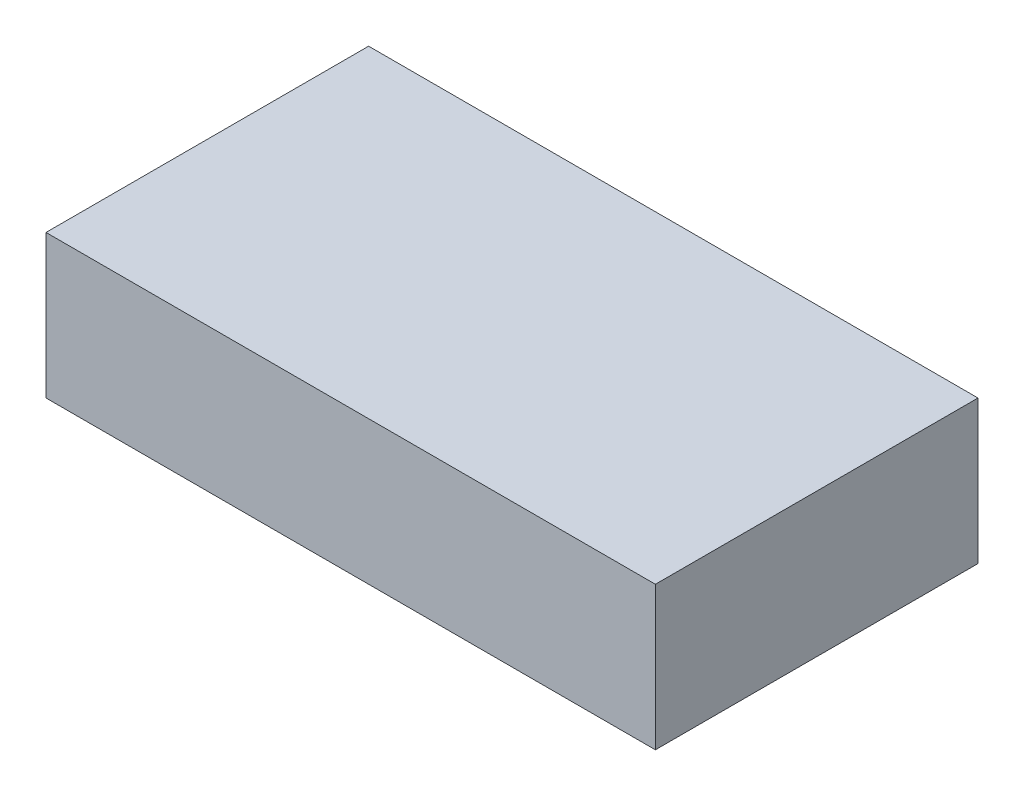
SolidWorks part; units mm, degrees
ref_plane "Front Plane" through (0, 0, 0) normal (0, 0, 1) x (1, 0, 0)
ref_plane "Top Plane" through (0, 0, 0) normal (0, 1, 0) x (1, 0, 0)
ref_plane "Right Plane" through (0, 0, 0) normal (1, 0, 0) x (0, 0, -1)
sketch "Sketch1" plane through (0, 0, 0) normal (0, 1, 0) x (1, 0, 0)
  line L1 (-107.95, 57.15) -> (107.95, 57.15)
  line L2 (-107.95, 57.15) -> (-107.95, -57.15)
  line L3 (-107.95, -57.15) -> (107.95, -57.15)
  line L4 (107.95, 57.15) -> (107.95, -57.15)
  line L5 (-107.95, 57.15) -> (107.95, -57.15) construction
  line L6 (-107.95, -57.15) -> (107.95, 57.15) construction
  point P0 (0, 0)
  dimension "D1" = 215.9
  dimension "D2" = 114.3
extrude "Boss-Extrude1" add sketch "Sketch1" along normal blind 50.8
